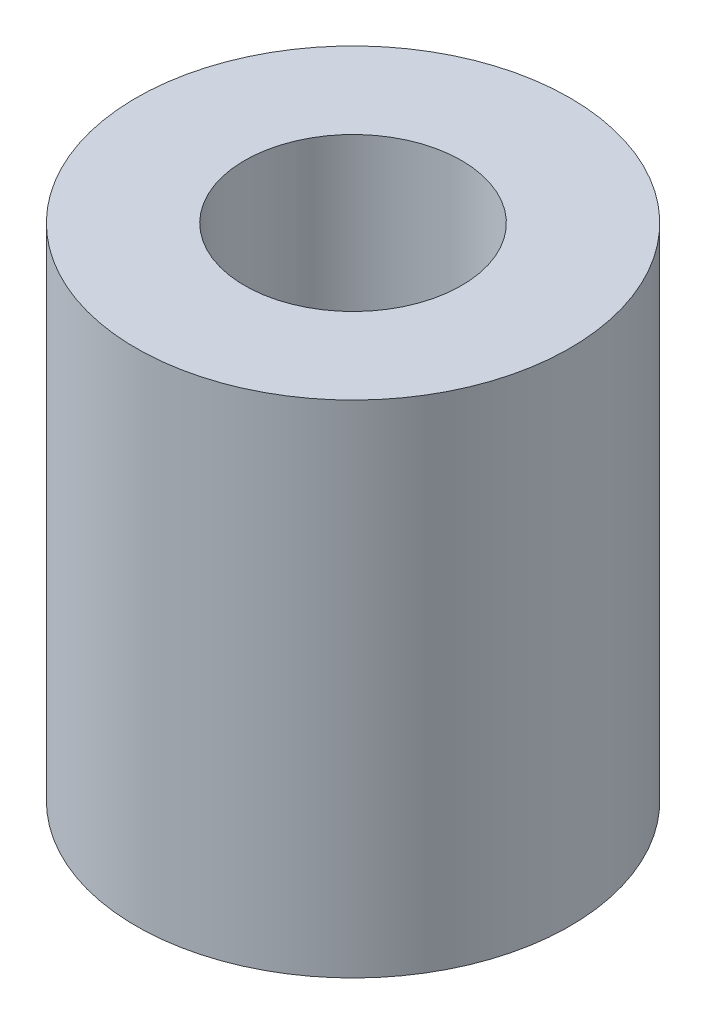
SolidWorks part; units mm, degrees
ref_plane "Front Plane" through (0, 0, 0) normal (0, 0, 1) x (1, 0, 0)
ref_plane "Top Plane" through (0, 0, 0) normal (0, 1, 0) x (1, 0, 0)
ref_plane "Right Plane" through (0, 0, 0) normal (1, 0, 0) x (0, 0, -1)
sketch "Sketch1" plane through (0, 0, 0) normal (0, 1, 0) x (1, 0, 0)
  circle A0 centre (0, 0) radius 3.302
  circle A1 centre (0, 0) radius 6.604
  dimension "D1" = 6.604
  dimension "D2" = 13.208
extrude "Boss-Extrude1" add sketch "Sketch1" along normal blind 15.24
